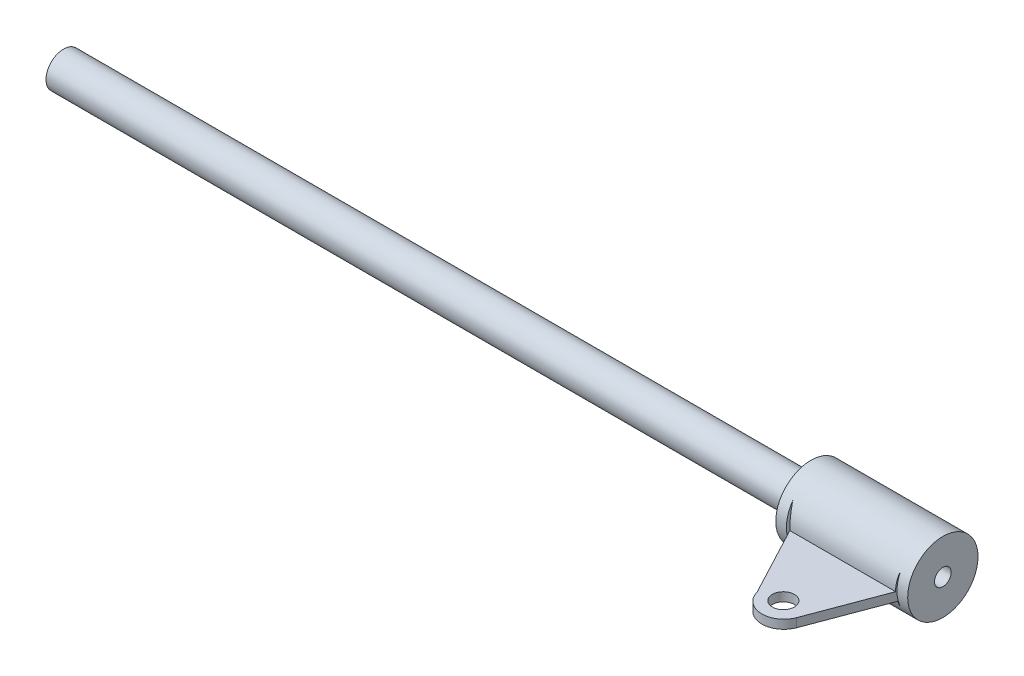
SolidWorks part; units mm, degrees
ref_plane "Front Plane" through (0, 0, 0) normal (0, 0, 1) x (1, 0, 0)
ref_plane "Top Plane" through (0, 0, 0) normal (0, 1, 0) x (1, 0, 0)
ref_plane "Right Plane" through (0, 0, 0) normal (1, 0, 0) x (0, 0, -1)
sketch "Sketch2" plane through (0, 0, 0) normal (0, 0, 1) x (1, 0, 0)
  line L1 (1650, -24.2452) -> (1350, -24.2452)
  line L2 (1650, -24.2452) -> (1650, 55.7548)
  line L3 (1650, 55.7548) -> (-350, 55.7548)
  line L4 (-350, 15.7548) -> (-350, 55.7548)
  line L7 (-350, 15.7548) -> (1350, 15.7548)
  line L8 (1350, -24.2452) -> (1350, 15.7548)
  point P0 (0, 0)
  dimension "D1" = 2000
  dimension "D3" = 1700
  dimension "D4" = 40
revolve "Revolve1" add sketch "Sketch2" angle 360 about L3
sketch "Sketch8" plane through (0, 0, 0) normal (0, 0, 1) x (1, 0, 0)
  line L0 (-559.9765, 43.1485) -> (1868.5885, 43.1485) construction
  line L2 (1625.3014, 53.1485) -> (1379.8613, 53.1485)
  line L3 (1625.3014, 53.1485) -> (1625.3014, 33.1485)
  line L4 (1625.3014, 33.1485) -> (1379.8613, 33.1485)
  line L5 (1379.8613, 53.1485) -> (1379.8613, 33.1485)
  line L6 (1625.3014, 53.1485) -> (1379.8613, 33.1485) construction
  line L7 (1625.3014, 33.1485) -> (1379.8613, 53.1485) construction
  point P2 (1502.5813, 43.1485)
  dimension "D1" = 20
extrude "Boss-Extrude1" add sketch "Sketch8" along normal blind 400
sketch "Sketch9" plane through (0, 0, 0) normal (0, 1, 0) x (1, 0, 0)
  line L0 (1476.7791, -258.9369) -> (1374.2777, -65.5004)
  line L1 (1374.2777, -65.5004) -> (1374.2777, -447.0603)
  line L2 (1374.2777, -447.0603) -> (1625.6336, -447.0603)
  line L3 (1625.6336, -447.0603) -> (1625.6336, -71.9119)
  line L4 (1625.6336, -71.9119) -> (1561.2109, -243.5699)
  circle A0 centre (1514.399, -226.0015) radius 50
  circle A1 centre (1512.6412, -225.4712) radius 25
  dimension "D1" = 100
  dimension "D2" = 50
extrude "Cut-Extrude8" cut sketch "Sketch9" against normal through all both and the other way through all contours A0 L0 L1 L2 L3 L4 | A1
sketch "Sketch10" plane through (0, 0, 0) normal (1, 0, 0) x (0, 0, -1)
  circle A0 centre (0, 55.7548) radius 19.05
  dimension "D1" = 38.1
extrude "Cut-Extrude9" cut sketch "Sketch10" against normal through all both and the other way through all
